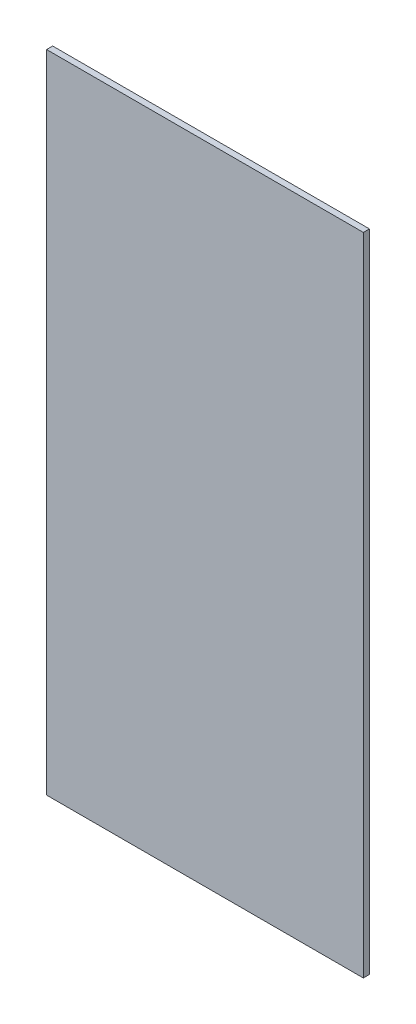
SolidWorks part; units mm, degrees
ref_plane "Plan de face" through (0, 0, 0) normal (0, 0, 1) x (1, 0, 0)
ref_plane "Plan de dessus" through (0, 0, 0) normal (0, 1, 0) x (1, 0, 0)
ref_plane "Plan de droite" through (0, 0, 0) normal (1, 0, 0) x (0, 0, -1)
sketch "Esquisse1" plane through (0, 0, 0) normal (0, 0, 1) x (1, 0, 0)
  line L1 (0.917, 196.4934) -> (156.917, 196.4934)
  line L2 (0.917, 196.4934) -> (0.917, -121.5066)
  line L3 (0.917, -121.5066) -> (156.917, -121.5066)
  line L4 (156.917, 196.4934) -> (156.917, -121.5066)
  dimension "D1" = 318
  dimension "D2" = 156
extrude "Boss.-Extru.1" add sketch "Esquisse1" along normal blind 3
